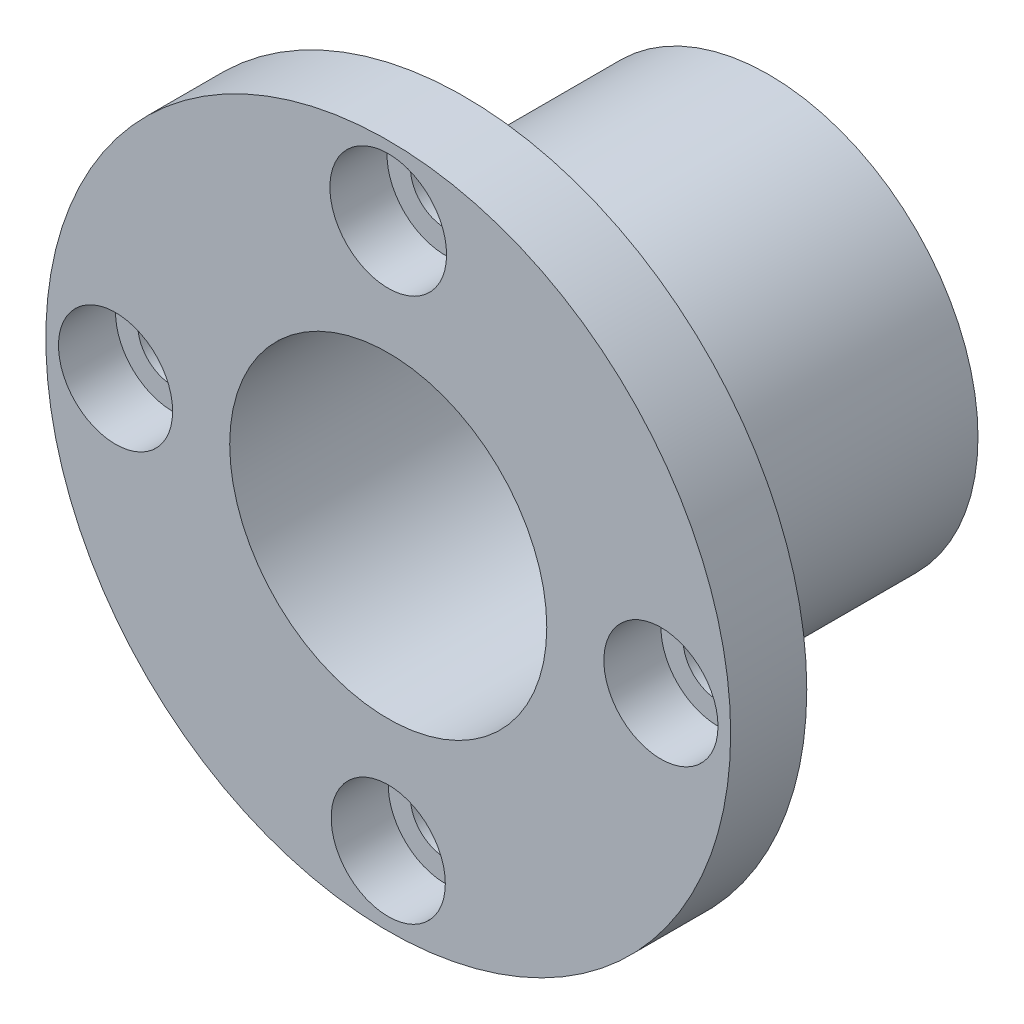
SolidWorks part; units mm, degrees
ref_plane "前视基准面" through (0, 0, 0) normal (0, 0, 1) x (1, 0, 0)
ref_plane "上视基准面" through (0, 0, 0) normal (0, 1, 0) x (1, 0, 0)
ref_plane "右视基准面" through (0, 0, 0) normal (1, 0, 0) x (0, 0, -1)
other "Configuration Table"
sketch "草图1" plane through (0, 0, 0) normal (0, 0, 1) x (1, 0, 0)
  circle A0 centre (0, 0) radius 12.5
  circle A1 centre (0, 0) radius 27
extrude "凸台-拉伸3" add sketch "草图1" along normal blind 6
sketch "草图2" plane through (0, 0, 0) normal (0, 0, -1) x (-1, 0, 0)
  circle A0 centre (0, 0) radius 16.5
  circle A1 centre (0, 0) radius 12.5
extrude "凸台-拉伸4" add sketch "草图2" along normal blind 24
sketch "草图3" plane through (0, 0, 6) normal (0, 0, 1) x (1, 0, 0)
  circle A1 centre (0, 21.5) radius 2.75
  circle A2 centre (21.5, 0) radius 2.75
  circle A3 centre (0, -21.5) radius 2.75
  circle A4 centre (-21.5, 0) radius 2.75
extrude "切除-拉伸1" cut sketch "草图3" against normal blind 24
sketch "草图4" plane through (0, 0, 6) normal (0, 0, 1) x (1, 0, 0)
  circle A0 centre (0, 21.5) radius 4.6
  circle A1 centre (21.5, 0) radius 4.5
  circle A2 centre (0, -21.5) radius 4.5
  circle A3 centre (-21.5, 0) radius 4.5
extrude "切除-拉伸2" cut sketch "草图4" against normal blind 4.5
